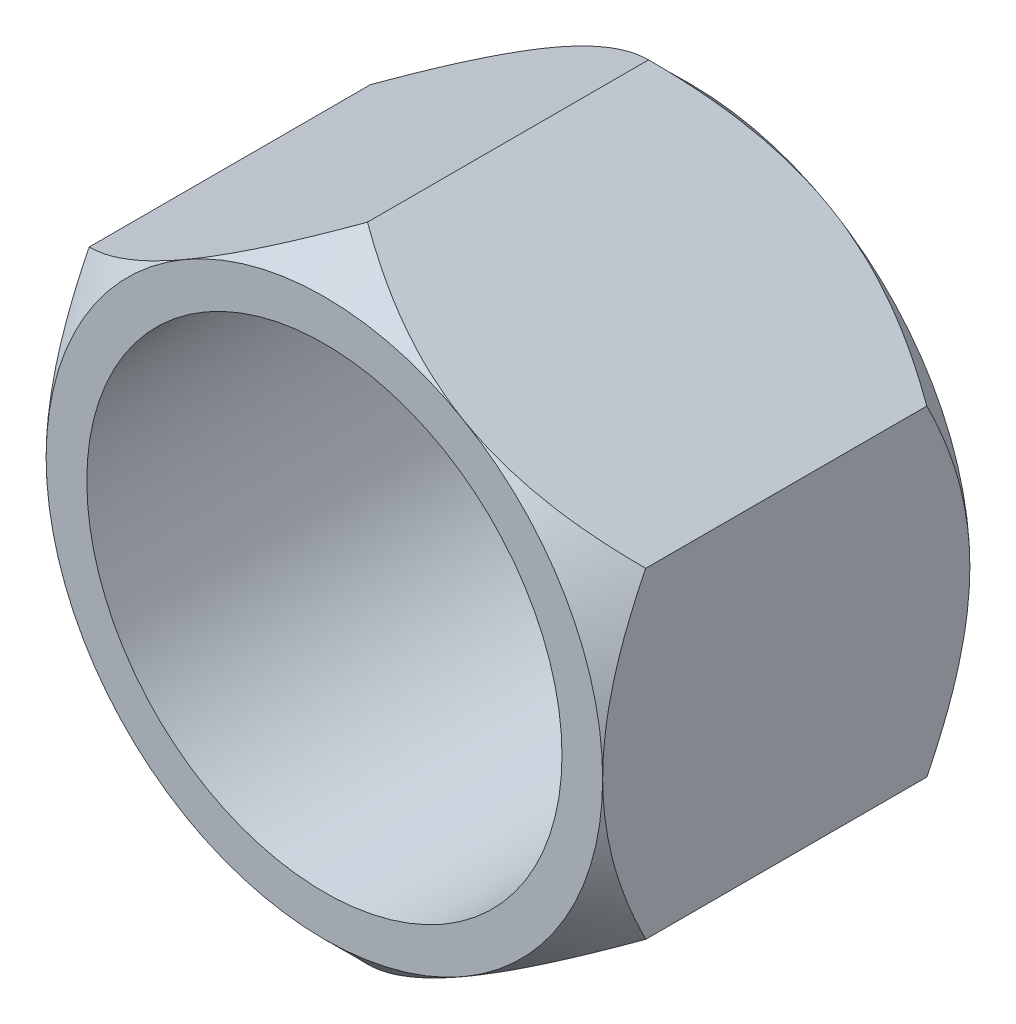
SolidWorks part; units mm, degrees
ref_plane "Front Plane" through (0, 0, 0) normal (0, 0, 1) x (1, 0, 0)
ref_plane "Top Plane" through (0, 0, 0) normal (0, 1, 0) x (1, 0, 0)
ref_plane "Right Plane" through (0, 0, 0) normal (1, 0, 0) x (0, 0, -1)
sketch "Sketch1" plane through (0, 0, 0) normal (0, 0, 1) x (1, 0, 0)
  line L0 (0, 0.2498) -> (0, -0.2069) construction
  line L1 (-0.4456, 0) -> (0.4185, 0) construction
  line L3 (0.1516, 0.0875) -> (0, 0.175)
  line L4 (0, 0.175) -> (-0.1516, 0.0875)
  line L5 (-0.1516, 0.0875) -> (-0.1516, -0.0875)
  line L6 (-0.1516, -0.0875) -> (0, -0.175)
  line L7 (0, -0.175) -> (0.1516, -0.0875)
  line L8 (0.1516, -0.0875) -> (0.1516, 0.0875)
  circle A0 centre (0, 0) radius 0.1516 construction
  circle A1 centre (0, 0) radius 0.1294
  dimension "D2" = 0.2588
  dimension "D1" = 0.35
extrude "Boss-Extrude2" add sketch "Sketch1" along normal blind 0.2
sketch "Sketch6" plane through (0, 0, 0.2) normal (0, 0, 1) x (1, 0, 0)
  line L0 (0.1516, 0.0875) -> (0, 0.175) construction
  circle A1 centre (0, 0) radius 0.1516
extrude "Cut-Extrude1" cut sketch "Sketch6" against normal blind 0.03 draft 45 flip side to cut
sketch "Sketch7" plane through (0, 0, 0) normal (0, 0, -1) x (-1, 0, 0)
  line L1 (0, 0.175) -> (0.1516, 0.0875) construction
  circle A0 centre (0, 0) radius 0.1516
extrude "Cut-Extrude2" cut sketch "Sketch7" against normal blind 0.03 draft 45 flip side to cut
